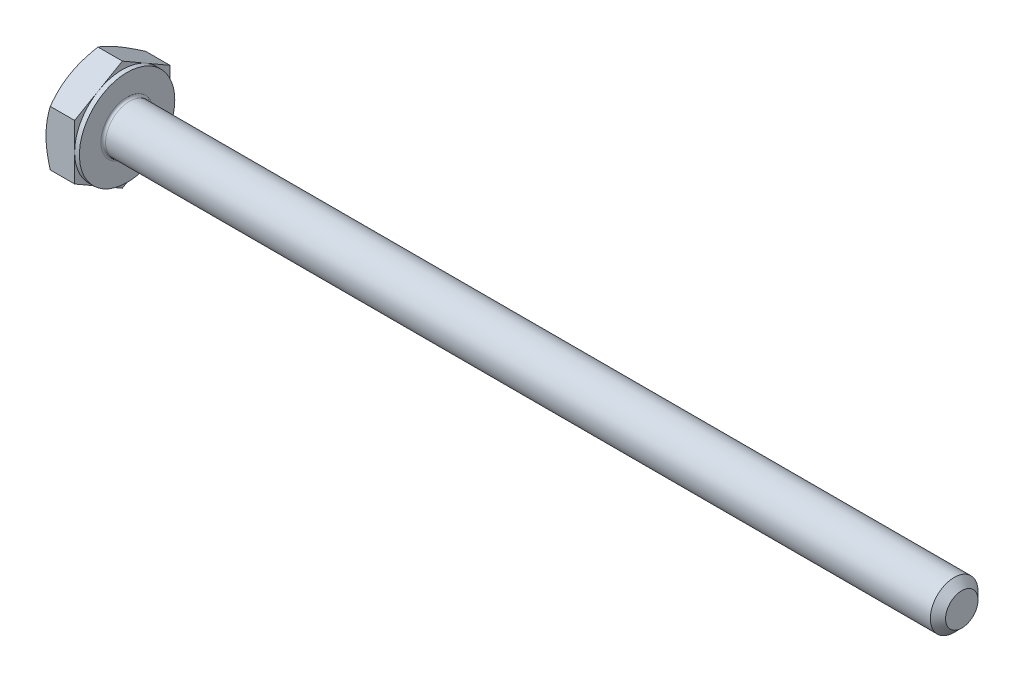
SolidWorks part; units mm, degrees
extrude "基体-拉伸" add sketch "草图1" along normal blind 1.4
sketch "草图1" plane through (0, 0, 0) normal (1, 0, 0) x (0, 0, -1)
  line L0 (2, 1.1547) -> (2, -1.1547)
  line L1 (-2, 1.1547) -> (-2, -1.1547)
  line L2 (2, -1.1547) -> (0, -2.3094)
  line L3 (0, -2.3094) -> (-2, -1.1547)
  line L4 (2, 1.1547) -> (0, 2.3094)
  line L5 (0, 2.3094) -> (-2, 1.1547)
  dimension "s" = 4
  dimension "D2" = 120
  dimension "D3" = 2
  dimension "D4" = 2
  dimension "D5" = 2
revolve "切除-旋转1" cut sketch "草图3" angle 360 about L6
sketch "草图3" plane through (0, 0, 0) normal (0, 0, 1) x (1, 0, 0)
  line L0 (0, 2) -> (3.0654, 7.3094)
  line L1 (0, 2.3094) -> (0, 1.1547) construction
  line L2 (3.0654, 7.3094) -> (3.0654, 12.3094)
  line L3 (3.0654, 12.3094) -> (-10, 12.3094)
  line L4 (-10, 12.3094) -> (-10, 2)
  line L5 (-10, 2) -> (0, 2)
  line L6 (0, 0) -> (99.06, 0) construction
  line L7 (1.4, 2.3094) -> (0, 2.3094) construction
  dimension "D1" = 2
  dimension "D2" = 5
  dimension "D3" = 10
  dimension "D4" = 5
  dimension "Head_ch_ang" = 30
revolve "凸台-旋转1" add sketch "草图2" angle 360 about L7
sketch "草图2" plane through (0, 0, 0) normal (0, 0, 1) x (1, 0, 0)
  line L0 (0, 1.1547) -> (0, -1.1547) construction
  line L1 (0, 0) -> (36.4, 0)
  line L2 (0, 0) -> (0, 1)
  line L3 (0, 1) -> (36.4, 1)
  line L4 (36.4, 0) -> (36.4, 0.6536)
  line L5 (1.4, 2.3094) -> (1.4, 1.1547) construction
  line L7 (0, 0) -> (96.52, 0) construction
  line L8 (36.4, -0.6536) -> (90.335, -1) construction
  line L9 (0, -1) -> (90.335, -1) construction
  line L10 (1.8, 15.24) -> (1.8, -1.27) construction
  line L11 (1.4, 15.24) -> (1.4, -1.27) construction
  line L12 (1.4, 1.1547) -> (1.4, -1.1547) construction
  line L14 (36.4, 1) -> (36.4, 0.6536)
  dimension "l" = 35
  dimension "m" = 2
  dimension "Minor_dia" = 1.3072
  dimension "p" = 0.4
  dimension "h" = 35
cosmetic thread "螺旋线1" parameters "Thread_length"=34.6, "Thread_minor"=1.3072
material "5.6级"
ref_plane "前视" through (0, 0, 0) normal (0, 0, 1) x (1, 0, 0)
ref_plane "上视" through (0, 0, 0) normal (0, 1, 0) x (1, 0, 0)
ref_plane "右视" through (0, 0, 0) normal (1, 0, 0) x (0, 0, -1)
sketch "草图5" plane through (0, 0, 0) normal (0, 0, 1) x (1, 0, 0)
  line L0 (1.4, 2) -> (-1.6654, 7.3094)
  line L1 (1.4, 2.3094) -> (1.4, 1.1547) construction
  line L2 (-1.6654, 7.3094) -> (-1.6654, 12.3094)
  line L3 (-1.6654, 12.3094) -> (8.3346, 12.3094)
  line L4 (8.3346, 12.3094) -> (8.3346, 2)
  line L5 (8.3346, 2) -> (1.4, 2)
  line L7 (1.4, 2.3094) -> (0.1786, 2.3094) construction
  line L8 (0, 0) -> (99.06, 0) construction
  line L9 (0, 0) -> (99.06, 0) construction
  dimension "D1" = 2
  dimension "D2" = 5
  dimension "D3" = 10
  dimension "D4" = 5
  dimension "Head_ch_ang" = 30
revolve "切除-旋转2" cut sketch "草图5" angle 360 about L8
sketch "草图4" plane through (0, 0, 0) normal (0, 0, 1) x (1, 0, 0)
  line L1 (1.4, 2.3094) -> (1.4, 1.1547) construction
  line L2 (1.4, 2) -> (1.2, 2)
  line L3 (1.4, 2) -> (1.4, 12.3094)
  line L4 (1.4, 12.3094) -> (1.2, 12.3094)
  line L5 (0, 0) -> (95.25, 0) construction
  line L6 (0, 0) -> (96.52, 0) construction
  line L7 (1.2, 2) -> (1.2, 12.3094)
  line L8 (1.2214, 2.3094) -> (0.1786, 2.3094) construction
  dimension "D2" = 10
  dimension "D1" = 4
revolve "切除-旋转3" cut sketch "草图4" angle 360 about L5
chamfer "倒角" distance 0.32 angle 45 1 edges at (36.4, 0, 1)
fillet "圆角" radius 0.1 1 edges at (1.4, 0, -1)
sketch "草图6" plane through (0, 0, 0) normal (0, 0, 1) x (1, 0, 0)
  line L0 (1.7, -0.6536) -> (1.5, -1)
  line L1 (1.7, -0.6536) -> (1.9, -1)
  line L2 (1.9, -1) -> (1.9, -1.25)
  line L3 (-3.175, 0) -> (5.1513, 0) construction
  line L5 (1.9, -1.25) -> (1.5, -1.25)
  line L6 (1.5, -1.25) -> (1.5, -1)
  arc A0 (1.5, -1) -> (1.4, -1.1) centre (1.5, -1.1) ccw construction
  dimension "Thread_minor" = 1.3072
  dimension "Diameter" = 2
revolve "切除-旋转4" [suppressed] cut sketch "草图6" angle 360 about L3
pattern_linear "阵列(线性)1" [suppressed]
equation "\"D3@草图1\" = \"s@草图1\" / 2"
equation "\"D4@草图1\" = \"D3@草图1\""
equation "\"D5@草图1\" = \"D4@草图1\""
equation "\"D1@草图3\" = \"s@草图1\" / 2"
equation "\"D1@草图5\" = \"s@草图1\" / 2"
equation "\"Head_ch_ang@草图5\" = \"Head_ch_ang@草图3\""
equation "\"D1@草图4\" = \"s@草图1\""
equation "\"Diameter@草图6\" = \"m@草图2\""
equation "\"Overcut@草图6\" = \"m@草图2\" * 1.25"
equation "\"Minor_dia@草图2\" = \"m@草图2\"-\"p@草图2\" * 1.732"
equation "\"Thread_minor@螺旋线1\" = \"Minor_dia@草图2\""
equation "\"Thread_minor@草图6\" = \"Minor_dia@草图2\""
equation "\"D1@倒角\" = \"p@草图2\"*0.8"
equation "\"Thread_length@螺旋线1\" = \"l@草图2\" - \"p@草图2\""
equation "\"Num_threads@阵列(线性)1\" = \"l@草图2\" / \"p@草图2\""
